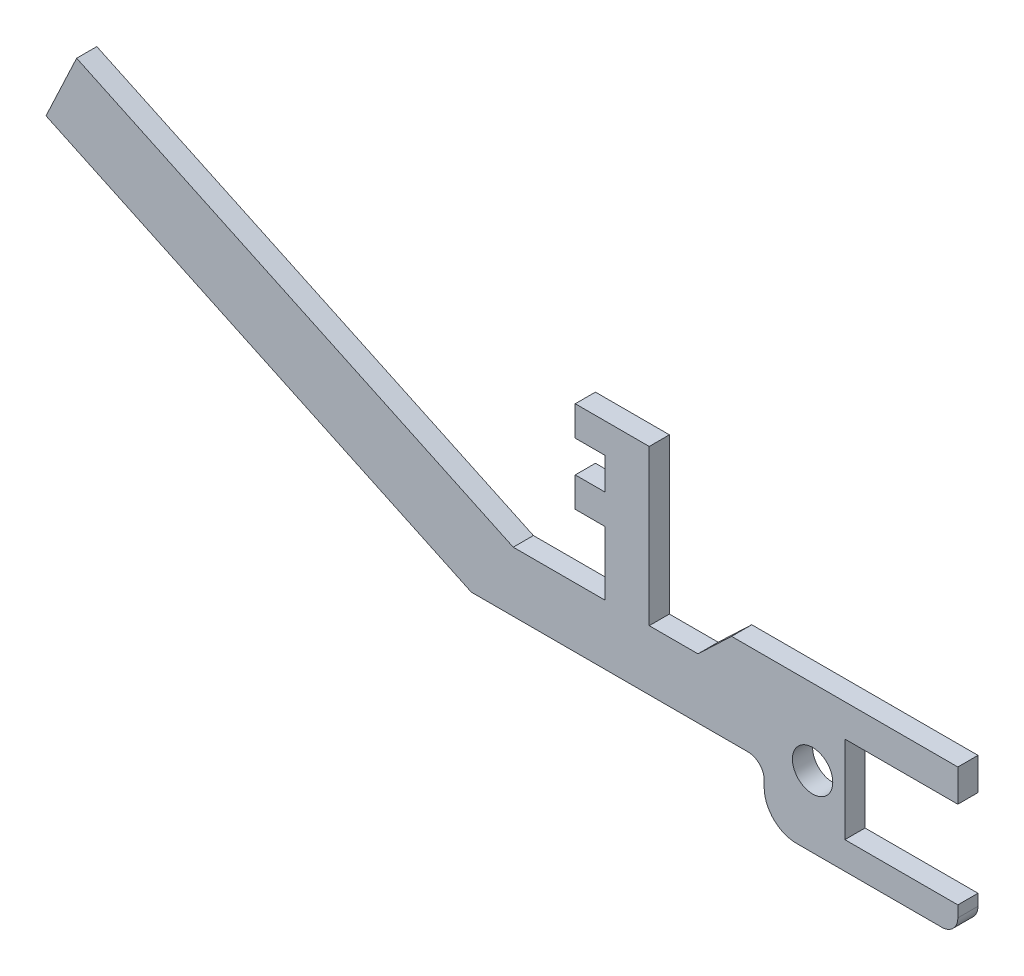
SolidWorks part; units mm, degrees
ref_plane "Front Plane" through (0, 0, 0) normal (0, 0, 1) x (1, 0, 0)
ref_plane "Top Plane" through (0, 0, 0) normal (0, 1, 0) x (1, 0, 0)
ref_plane "Right Plane" through (0, 0, 0) normal (1, 0, 0) x (0, 0, -1)
sketch "Sketch1" plane through (0, 0, 0) normal (0, 0, 1) x (1, 0, 0)
  line L0 (-16.3258, 3.4552) -> (-23.5589, 3.4552)
  line L1 (-16.3258, 10.8222) -> (-18.6789, 10.8222)
  line L2 (-18.6789, 15.6724) -> (-12.8574, 15.6724)
  line L3 (-12.8574, 15.6724) -> (-12.8574, 3.4552)
  line L4 (-12.8574, 3.4552) -> (-9.0205, 3.4552)
  line L5 (-9.0205, 3.4552) -> (-6.3743, 5.969)
  line L6 (-6.3743, 5.969) -> (11.43, 5.969)
  line L7 (11.43, 5.969) -> (11.43, 3.429)
  line L8 (11.43, 3.429) -> (2.54, 3.429)
  line L9 (2.54, 3.429) -> (2.54, -3.429)
  line L10 (2.54, -3.429) -> (11.43, -3.429)
  line L11 (11.43, -3.429) -> (11.43, -4.318)
  line L12 (10.16, -5.588) -> (-1.27, -5.588)
  line L13 (-3.81, -3.048) -> (-3.81, -2.5296)
  line L14 (-5.08, -1.2596) -> (-26.8556, -1.2596)
  line L15 (-26.8556, -1.2596) -> (-60.3304, 14.4695)
  line L16 (-60.3304, 14.4695) -> (-57.9195, 19.6005)
  line L17 (0, 0) -> (2.54, 0) construction
  line L18 (-23.5589, 3.4552) -> (-57.9195, 19.6005)
  line L19 (-16.3258, 10.8222) -> (-16.3258, 13.3247)
  line L20 (-16.3258, 13.3247) -> (-18.6789, 13.3247)
  line L21 (-18.6789, 13.3247) -> (-18.6789, 15.6724)
  line L22 (-18.6789, 10.8222) -> (-18.6789, 8.4745)
  line L23 (-18.6789, 8.4745) -> (-16.3258, 8.4745)
  line L24 (-16.3258, 8.4745) -> (-16.3258, 3.4552)
  circle A0 centre (0, 0) radius 1.5875
  arc A1 (-1.27, -5.588) -> (-3.81, -3.048) centre (-1.27, -3.048) cw
  arc A2 (-5.08, -1.2596) -> (-3.81, -2.5296) centre (-5.08, -2.5296) cw
  arc A3 (11.43, -4.318) -> (10.16, -5.588) centre (10.16, -4.318) cw
  dimension "D1" = 3.175
  dimension "D7" = 2.54
  dimension "D8" = 1.27
  dimension "D2" = 6.858
  dimension "D3" = 11.43
  dimension "D4" = 3.81
  dimension "D5" = 5.588
  dimension "D6" = 8.89
  dimension "D9" = 2.54
extrude "Boss-Extrude1" add sketch "Sketch1" along normal blind 1.5875
